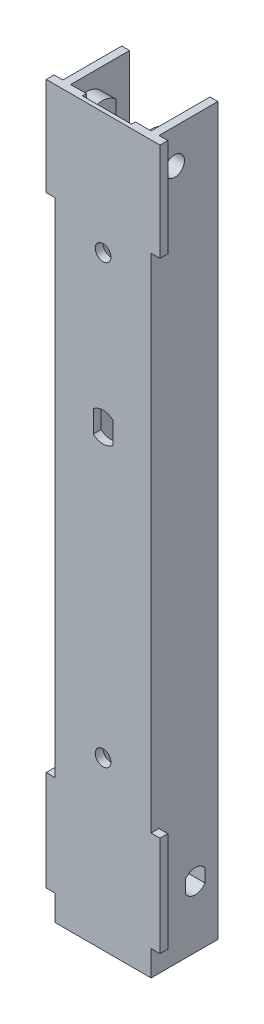
SolidWorks part; units mm, degrees
ref_plane "Front Plane" through (0, 0, 0) normal (0, 0, 1) x (1, 0, 0)
ref_plane "Top Plane" through (0, 0, 0) normal (0, 1, 0) x (1, 0, 0)
ref_plane "Right Plane" through (0, 0, 0) normal (1, 0, 0) x (0, 0, -1)
sketch "Sketch3" plane through (0, 0, 0) normal (0, 1, 0) x (1, 0, 0)
  line L0 (0, 0) -> (-49, 0)
  line L1 (-49, 0) -> (-49, 34)
  line L2 (-49, 34) -> (-45, 34)
  line L3 (-45, 34) -> (-45, 4)
  line L4 (-45, 4) -> (-4, 4)
  line L5 (-4, 4) -> (-4, 34)
  line L6 (-4, 34) -> (0, 34)
  line L7 (0, 34) -> (0, 0)
  line L8 (-45, 34) -> (-4, 34) construction
  dimension "D1" = 4
  dimension "D2" = 4
  dimension "D3" = 34
  dimension "D4" = 49
extrude "Boss-Extrude1" add sketch "Sketch3" along normal blind 370
sketch "Sketch9" plane through (0, 0, 0) normal (0, 0, 1) x (1, 0, 0)
  line L0 (-24.5, 370) -> (-24.5, 0) construction
  line L1 (-53.5, 370) -> (4.5, 370)
  line L2 (-53.5, 370) -> (-53.5, 320)
  line L3 (-53.5, 320) -> (4.5, 320)
  line L4 (4.5, 370) -> (4.5, 320)
  line L5 (-49, 0) -> (0, 0) construction
  line L6 (-49, 370) -> (0, 370) construction
  line L8 (-53.5, 64) -> (4.5, 64)
  line L9 (-53.5, 64) -> (-53.5, 13)
  line L10 (-53.5, 13) -> (4.5, 13)
  line L11 (4.5, 64) -> (4.5, 13)
  dimension "D1" = 58
  dimension "D2" = 50
  dimension "D3" = 51
  dimension "D4" = 13
extrude "Boss-Extrude2" add sketch "Sketch9" against normal blind 4
ref_plane "Plane1" through (-24.5, 0, 0) normal (1, 0, 0) x (0, 0, -1)
sketch "Sketch14" plane through (0, 0, 0) normal (1, 0, 0) x (0, 0, -1)
  line L0 (0, 192) -> (22.5, 192) construction
  line L1 (0, 320) -> (0, 64) construction
  line L2 (22.5, 192) -> (22.5, 31.5) construction
  line L3 (12, 192) -> (12, 352.5) construction
  line L4 (19, 360.0558) -> (19, 344.9442)
  line L5 (5, 360.0558) -> (5, 344.9442)
  line L6 (29.5, 38.5) -> (29.5, 27.627)
  line L7 (28.5, 39.5) -> (22.5, 39.5)
  line L8 (27.5, 34.8166) -> (27.5, 28.1834)
  line L9 (17.5, 34.8166) -> (17.5, 28.1834)
  line L10 (22.5, 37.5) -> (22.5, 25.5) construction
  line L11 (22.5, 31.5) -> (17.5, 31.5) construction
  line L12 (28.5, 39.5) -> (29.5, 38.5)
  arc A0 (27.5, 34.8166) -> (17.5, 34.8166) centre (22.5, 31.5) ccw
  circle A1 centre (12, 352.5) radius 5
  arc A2 (5, 344.9442) -> (19, 344.9442) centre (12, 352.5) ccw
  arc A3 (19, 360.0558) -> (5, 360.0558) centre (12, 352.5) ccw
  arc A5 (17.5, 28.1834) -> (27.5, 28.1834) centre (22.5, 31.5) ccw
  arc A6 (22.5, 39.5) -> (29.5, 27.627) centre (22.5, 31.5) ccw
  point P14 (29.5, 39.5)
  dimension "D4" = 10
  dimension "D5" = 12
  dimension "D7" = 10.3
  dimension "D1" = 22.5
  dimension "D2" = 12
  dimension "D3" = 321
  dimension "D6" = 7
  dimension "D8" = 5
  dimension "D9" = 7
  dimension "D10" = 8
extrude "Boss-Extrude3" add sketch "Sketch14" against normal up to surface (49 mm away) up to face at (-49, 153.4, -8.4)
sketch "Sketch15" plane through (0, 0, -34) normal (0, 0, -1) x (-1, 0, 0)
  line L0 (24.5, 370) -> (24.5, 0) construction
  line L1 (4, 370) -> (45, 370) construction
  line L2 (4, 0) -> (45, 0) construction
  line L4 (12, 370) -> (37, 370)
  line L5 (12, 370) -> (12, 340)
  line L6 (12, 340) -> (37, 340)
  line L7 (37, 370) -> (37, 340)
  line L8 (9.5, 0) -> (39.5, 0)
  line L9 (9.5, 0) -> (9.5, 67.1885)
  line L10 (9.5, 67.1885) -> (39.5, 67.1885)
  line L11 (39.5, 0) -> (39.5, 67.1885)
  point P10 (24.5, 340)
  point P15 (24.5, 0)
  dimension "D1" = 25
  dimension "D2" = 30
  dimension "D3" = 30
extrude "Cut-Extrude4" cut sketch "Sketch15" against normal up to surface (30 mm away) up to face at (-24.5, 185, -4)
sketch "Sketch16" plane through (0, 0, -4) normal (0, 0, -1) x (-1, 0, 0)
  line L0 (24.5, 370) -> (24.5, 0) construction
  line L1 (4, 370) -> (45, 370) construction
  line L2 (4, 0) -> (45, 0) construction
  circle A0 centre (24.5, 85) radius 4
  circle A1 centre (24.5, 308) radius 4
  dimension "D1" = 8
  dimension "D2" = 85
  dimension "D4" = 8
  dimension "D3" = 223
extrude "Cut-Extrude5" cut sketch "Sketch16" against normal through all
sketch "Sketch17" plane through (0, 0, -4) normal (0, 0, -1) x (-1, 0, 0)
  line L0 (4, 352.5) -> (45, 352.5) construction
  line L1 (4, 347.5) -> (4, 357.5) construction
  line L2 (45, 370) -> (45, 0) construction
  line L3 (24.5, 352.5) -> (24.5, 231) construction
  line L4 (19.5, 236.5902) -> (19.5, 225.4098)
  line L5 (29.5, 236.5902) -> (29.5, 225.4098)
  arc A0 (19.5, 225.4098) -> (29.5, 225.4098) centre (24.5, 231) ccw
  arc A1 (29.5, 236.5902) -> (19.5, 236.5902) centre (24.5, 231) ccw
  dimension "D1" = 15
  dimension "D2" = 5
  dimension "D3" = 121.5
extrude "Cut-Extrude6" cut sketch "Sketch17" against normal through all
sketch "Sketch18" plane through (-45, 0, 0) normal (1, 0, 0) x (0, 0, -1)
  line L2 (17.5, 34.8166) -> (17.5, 28.1834)
  line L3 (27.5, 28.1834) -> (27.5, 34.8166)
  line L4 (17.5, 34.8166) -> (17.5, 28.1834)
  line L5 (27.5, 28.1834) -> (27.5, 34.8166)
  circle A1 centre (12, 352.5) radius 5
  arc A2 (17.5, 28.1834) -> (27.5, 28.1834) centre (22.5, 31.5) ccw
  arc A3 (27.5, 34.8166) -> (17.5, 34.8166) centre (22.5, 31.5) ccw
  arc A4 (17.5, 28.1834) -> (27.5, 28.1834) centre (22.5, 31.5) ccw
  arc A5 (27.5, 34.8166) -> (17.5, 34.8166) centre (22.5, 31.5) ccw
  circle A6 centre (12, 352.5) radius 5
  dimension "D1" = 0
  dimension "D2" = 0
extrude "Cut-Extrude7" cut sketch "Sketch18" along normal through all and the other way through all
sketch "Sketch19" plane through (-24.5, 0, 0) normal (1, 0, 0) x (0, 0, -1)
  line L0 (2, 370) -> (2, 320) construction
  line L1 (4, 370) -> (0, 370) construction
  line L2 (4, 320) -> (0, 320) construction
  line L3 (2, 370) -> (2, 354.1844) construction
  line L4 (4, 370) -> (4, 338.5)
  line L5 (4, 320) -> (4, 370) construction
  line L6 (12, 352.5) -> (2, 352.5) construction
  line L7 (4, 370) -> (2, 370)
  line L8 (2, 370) -> (2, 354.1844)
  arc A0 (2, 354.1844) -> (4, 338.5) centre (64.5, 354.1844) ccw
  dimension "D1" = 125
  dimension "D2" = 14
extrude "Cut-Extrude8" cut sketch "Sketch19" against normal mid plane 25
